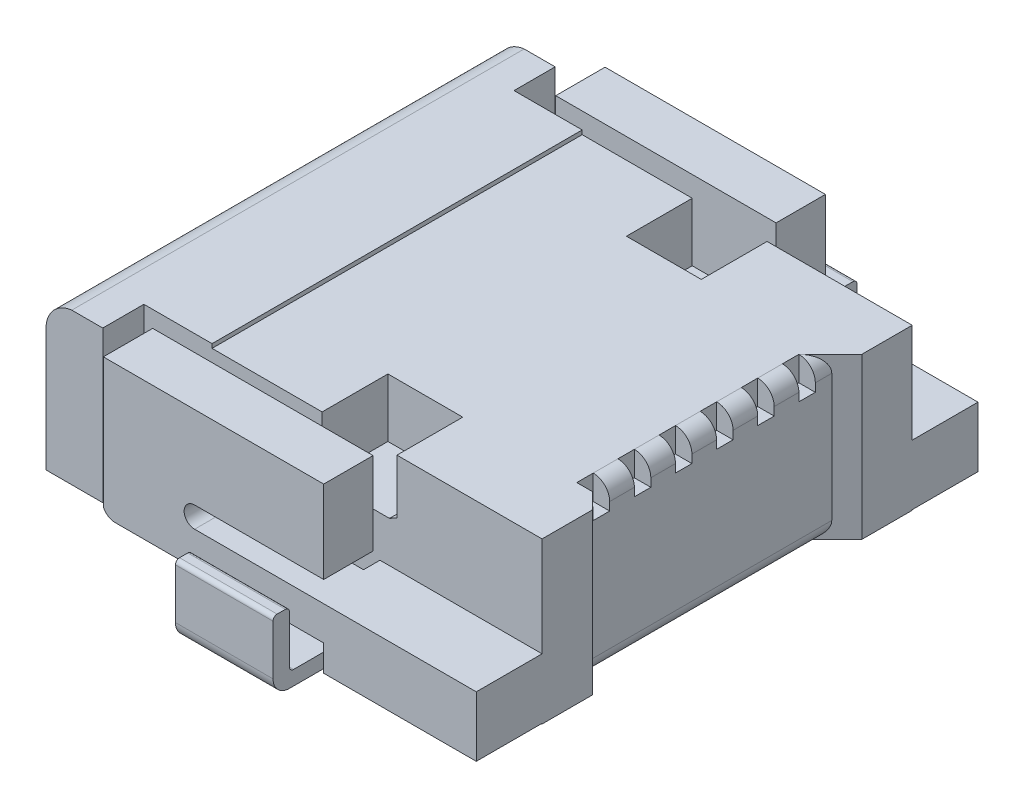
SolidWorks part; units mm, degrees
ref_plane "Front Plane" through (0, 0, 0) normal (0, 0, 1) x (1, 0, 0)
ref_plane "Top Plane" through (0, 0, 0) normal (0, 1, 0) x (1, 0, 0)
ref_plane "Right Plane" through (0, 0, 0) normal (1, 0, 0) x (0, 0, -1)
sketch "Sketch5" plane through (0, 0, 0) normal (0, 0, 1) x (1, 0, 0)
  line L0 (40.6667, 46) -> (203.3333, 46) construction
  line L1 (1.0365, 0.0671) -> (5.5705, 0.0671)
  line L2 (5.5705, 0.0671) -> (5.5705, 2.0592)
  line L3 (5.5705, 2.0592) -> (1.0365, 2.0592)
  line L4 (1.0365, 2.0592) -> (1.0365, 0.0671)
  line L5 (1.0365, 0.9096) -> (0.7294, 0.9096)
  line L6 (0.7294, 0.9096) -> (0.7294, 2.0592)
  line L7 (0.7294, 2.0592) -> (1.0365, 2.0592)
  line L8 (2.4126, 0.8573) -> (2.4126, 0.0671)
  line L9 (2.4126, 0.8573) -> (3.5997, 0.8573)
  line L10 (3.5997, 0.8573) -> (3.5997, 0.0671)
  line L11 (3.5997, 0.7994) -> (5.5705, 0.7994)
  line L12 (2.4126, 0.7994) -> (2.1463, 0.7994)
  line L13 (2.1463, 1.0542) -> (3.7156, 1.0542)
  line L14 (3.7156, 1.0542) -> (3.7156, 2.0592)
  line L15 (2.4126, 0.175) -> (1.0365, 0.175)
  line L16 (3.5997, 0.175) -> (5.5705, 0.175)
  line L17 (2.4126, 0.3858) -> (1.1847, 0.3858)
  line L18 (0.0415, 1.6702) -> (0.0415, 0.2199)
  line L19 (0.0415, 0.2199) -> (0.7294, 0.2199)
  line L20 (0.7294, 0.2199) -> (0.7294, 0.9096)
  line L21 (0.7294, 2.0592) -> (0.3527, 2.0592)
  line L22 (3.8064, 2.0592) -> (3.8064, 1.3482)
  line L23 (3.8064, 1.3482) -> (3.7156, 1.2979)
  line L24 (0.9408, 0.9096) -> (0.9408, 1.2134)
  line L25 (0.9408, 1.2134) -> (1.0365, 1.2134)
  line L26 (3.5997, 0.3858) -> (3.7156, 0.3858)
  line L27 (3.7156, 0.3858) -> (3.7156, 0.175)
  arc A0 (2.1463, 0.7994) -> (2.1463, 1.0542) centre (2.1463, 0.9268) cw
  arc A1 (0.0415, 1.6702) -> (0.3527, 2.0592) centre (0.3916, 1.7091) cw
  spline S0 degree 2 poles (1.1847, 0.3858) (1.082, 0.3886) (1.0365, 0.477) knots 0 0 0 1 1 1
extrude "Boss-Extrude1" add sketch "Sketch5" against normal blind 0.6 contours S0 L17 L8 L12 A0 L13 L14 L3 L4
sketch "Sketch7" plane through (0, 0, 0) normal (0, 0, 1) x (1, 0, 0)
  line L0 (5.5705, 0.0671) -> (5.5705, 2.0592) construction
  line L2 (3.7156, 0.3858) -> (3.7156, 0.175) construction
  line L3 (3.5997, 0.3858) -> (3.7156, 0.3858) construction
  line L4 (3.5997, 0.7994) -> (5.5705, 0.7994) construction
  line L10 (5.5705, 0.175) -> (5.5705, 0.7994)
  line L11 (3.7156, 0.175) -> (3.7156, 0.0671)
  line L12 (3.7156, 0.3858) -> (3.7156, 0.175)
  line L13 (3.5997, 0.3858) -> (3.7156, 0.3858)
  line L14 (3.5997, 0.7994) -> (5.5705, 0.7994)
  line L15 (3.5997, 0.7994) -> (3.5997, 0.3858)
  line L16 (1.0365, 0.0671) -> (5.5705, 0.0671) construction
  line L17 (3.7156, 0.0671) -> (5.5705, 0.0671)
  line L18 (5.5705, 0.0671) -> (5.5705, 0.175)
  line L20 (2.4126, 0.3858) -> (3.5997, 0.3858)
  line L21 (2.4126, 0.7994) -> (3.5997, 0.7994)
  line L24 (2.4126, 0.7994) -> (2.4126, 0.3858)
extrude "Boss-Extrude2" add sketch "Sketch7" against normal blind 0.8 separate body contours L17 L18 L10 L14 L15 L13 L12 L11
sketch "Sketch8" plane through (0, 0, 0) normal (0, 0, 1) x (1, 0, 0)
  line L0 (3.5997, 0.7994) -> (2.4126, 0.7994)
  line L1 (3.5997, 0.3858) -> (2.4126, 0.3858)
  line L2 (3.5997, 0.8573) -> (3.5997, 0.0671) construction
  line L3 (2.4126, 0.8573) -> (2.4126, 0.0671) construction
  line L4 (3.5997, 0.7994) -> (3.5997, 0.3858)
  line L5 (2.4126, 0.7994) -> (2.4126, 0.3858)
extrude "Boss-Extrude3" add sketch "Sketch8" against normal blind 0.6
sketch "Sketch11" plane through (0, 0, 0) normal (0, 1, 0) x (1, 0, 0)
  line L0 (5.5705, 0.8) -> (5.5705, 1.4131)
  line L1 (5.5705, 1.4131) -> (5.3077, 1.5403)
  line L2 (5.3077, 1.5403) -> (5.3077, 9.05)
  line L3 (3.5997, 0) -> (5.5705, 0) construction
  line L4 (5.3077, 9.05) -> (1.7077, 9.05)
  line L5 (1.7077, 9.05) -> (1.7077, 0.8)
  line L6 (1.7077, 0.8) -> (5.5705, 0.8)
  dimension "D1" = 9.05
  dimension "D2" = 3.6
ref_plane "Plane1" through (0, 0.06, 0) normal (0, 1, 0) x (1, 0, 0)
sketch "Sketch13" plane through (0, 0.06, 0) normal (0, 1, 0) x (1, 0, 0)
  line L0 (3.7156, 0) -> (1.0365, 0) construction
  line L2 (5.5705, 0.8) -> (5.5705, 1.4131) construction
  line L6 (5.3077, 3.05) -> (1.6924, 3.05)
  line L7 (5.5705, 1.4131) -> (5.3881, 1.5955)
  line L8 (5.5705, 0.8) -> (5.5705, 1.4131)
  line L9 (1.6924, 3.05) -> (1.6924, 0.8)
  line L10 (5.3881, 1.5955) -> (5.3881, 3.05)
  line L11 (1.6924, 0.8) -> (5.5705, 0.8)
  line L12 (5.3881, 3.05) -> (5.3077, 3.05)
  dimension "D1" = 3.05
extrude "Boss-Extrude5" add sketch "Sketch13" along normal up to surface (1.9992 mm away) up to face at (2.376, 2.0592, -0.3)
sketch "Sketch17" plane through (0, 0, -0.8) normal (0, 0, 1) x (1, 0, 0)
  line L0 (3.8064, 1.3482) -> (3.7156, 1.2979) construction
  line L1 (3.8064, 2.0592) -> (3.8064, 1.3482) construction
  line L2 (3.8064, 1.3482) -> (3.7156, 1.2979)
  line L3 (3.8064, 2.0592) -> (3.8064, 1.3482)
  line L4 (3.7156, 1.2979) -> (2.8963, 1.2979)
  line L5 (2.8963, 1.2979) -> (2.8963, 2.0592)
  line L6 (1.6924, 2.0592) -> (5.5705, 2.0592) construction
  line L7 (2.8963, 2.0592) -> (3.8064, 2.0592)
extrude "Cut-Extrude6" cut sketch "Sketch17" against normal blind 0.8
sketch "Sketch18" plane through (0, 0, -0.8) normal (0, 0, 1) x (1, 0, 0)
  line L0 (0.0415, 1.6702) -> (0.0415, 0.2199)
  line L1 (0.7294, 2.0592) -> (0.7294, 0.9096)
  line L5 (0.0415, 0.2199) -> (0.7294, 0.2199) construction
  line L6 (0.7294, 0.2199) -> (0.7294, 0.9096) construction
  line L9 (0.7294, 2.0592) -> (0.3527, 2.0592) construction
  line L15 (0.0415, 0.2199) -> (0.7294, 0.2199)
  line L16 (0.7294, 0.2199) -> (0.7294, 0.9096)
  line L19 (0.7294, 2.0592) -> (0.3527, 2.0592)
  arc A0 (0.3527, 2.0592) -> (0.0415, 1.6702) centre (0.3916, 1.7091) ccw construction
  arc A1 (0.3527, 2.0592) -> (0.0415, 1.6702) centre (0.3916, 1.7091) ccw
sketch "Sketch19" plane through (1.6924, 0, 0) normal (-1, 0, 0) x (0, 0, 1)
  line L0 (-3.05, 2.0592) -> (-0.8, 2.0592) construction
  line L1 (-3.05, 2.0592) -> (-0.8, 2.0592)
  line L4 (-0.8, 2.0592) -> (-3.05, 2.0592)
  line L5 (-3.05, 2.0592) -> (-3.05, 0.06)
  line L6 (-3.05, 0.06) -> (-0.8, 0.06)
  line L7 (-0.8, 0.06) -> (-0.8, 2.0592)
  line L9 (-3.05, 2.0592) -> (-3.05, 0.06)
  line L10 (-3.05, 0.06) -> (-0.8, 0.06)
  line L11 (-0.8, 0.06) -> (-0.8, 2.0592)
  dimension "D1" = 0
extrude "Boss-Extrude6" add sketch "Sketch19" along normal up to vertex (0.963 mm away) separate body up to point (0.7294, 2.0592, -0.8)
extrude "Boss-Extrude7" add sketch "Sketch18" against normal up to surface (2.25 mm away) up to face at (3.5403, 1.0596, -3.05)
sketch "Sketch20" plane through (0, 0, -0.8) normal (0, 0, 1) x (1, 0, 0)
  line L0 (1.0365, 2.0592) -> (1.0365, 0.0671) construction
  line L1 (0.7294, 0.2199) -> (0.7294, 0.9096) construction
  line L2 (1.0365, 0.9096) -> (0.7294, 0.9096) construction
  line L3 (1.0365, 2.0592) -> (1.0365, 0.0671)
  line L4 (0.7294, 0.2199) -> (0.7294, 0.9096)
  line L5 (1.0365, 0.9096) -> (0.7294, 0.9096)
  line L6 (0.7294, 0.2199) -> (0.7294, 0.06)
  line L7 (0.7294, -0.0203) -> (1.0365, -0.0203)
  line L8 (1.0365, -0.0203) -> (1.0365, 0.0671)
  line L9 (0.7294, 0.06) -> (0.7294, -0.0203)
extrude "Cut-Extrude7" cut sketch "Sketch20" against normal up to surface (2.25 mm away)
sketch "Sketch21" plane through (0, 0, -0.8) normal (0, 0, 1) x (1, 0, 0)
  line L0 (0.7294, 0.2199) -> (0.7294, 0.9096) construction
  line L1 (0.0415, 0.2199) -> (0.7294, 0.2199) construction
  line L2 (0.0415, 1.6702) -> (0.0415, 0.2199) construction
  line L3 (0.7294, 2.0592) -> (0.3527, 2.0592) construction
  line L4 (0.7294, 0.9096) -> (0.7294, 2.0592) construction
  line L5 (0.7294, 0.2199) -> (0.7294, 0.9096)
  line L6 (0.0415, 0.2199) -> (0.7294, 0.2199)
  line L7 (0.0415, 1.6702) -> (0.0415, 0.2199)
  line L8 (0.7294, 2.0592) -> (0.3527, 2.0592)
  line L9 (0.7294, 0.9096) -> (0.7294, 2.0592)
  arc A0 (0.3527, 2.0592) -> (0.0415, 1.6702) centre (0.3916, 1.7091) ccw construction
  arc A1 (0.3527, 2.0592) -> (0.0415, 1.6702) centre (0.3916, 1.7091) ccw
extrude "Boss-Extrude8" add sketch "Sketch21" along normal blind 0.5
mirror "Mirror1" of "Boss-Extrude8", "Cut-Extrude7", "Boss-Extrude7", "Boss-Extrude6", "Cut-Extrude6", "Boss-Extrude5", "Boss-Extrude3", "Boss-Extrude2", "Boss-Extrude1"
sketch "Sketch22" plane through (0, 2.0592, 0) normal (0, 1, 0) x (1, 0, 0)
  line L0 (1.5582, 5.3) -> (1.5582, 0.8)
  line L20 (2.8963, 4.5) -> (2.8963, 5.3)
  line L21 (2.8963, 5.3) -> (0.7294, 5.3)
  line L22 (0.7294, 5.3) -> (0.7294, 5.8)
  line L23 (0.7294, 5.8) -> (0.3527, 5.8)
  line L24 (0.3527, 5.8) -> (0.3527, 0.3)
  line L25 (0.3527, 0.3) -> (0.7294, 0.3)
  line L26 (0.7294, 0.3) -> (0.7294, 0.8)
  line L27 (0.7294, 0.8) -> (2.8963, 0.8)
  line L28 (2.8963, 0.8) -> (2.8963, 1.6)
  line L29 (2.8963, 1.6) -> (3.8064, 1.6)
  line L30 (3.8064, 1.6) -> (3.8064, 0.8)
  line L31 (3.8064, 0.8) -> (5.5705, 0.8)
  line L32 (5.5705, 0.8) -> (5.5705, 1.4131)
  line L33 (5.5705, 1.4131) -> (5.3881, 1.5955)
  line L34 (5.5705, 1.4131) -> (5.3881, 1.5955)
  line L35 (5.3881, 1.5955) -> (5.3881, 4.5045)
  line L36 (5.5705, 4.6869) -> (5.5705, 5.3)
  line L37 (5.5705, 5.3) -> (3.8064, 5.3)
  line L38 (3.8064, 5.3) -> (3.8064, 4.5)
  line L39 (3.8064, 4.5) -> (2.8963, 4.5)
  line L40 (2.8963, 4.5) -> (2.8963, 5.3)
  line L41 (2.8963, 5.3) -> (1.5582, 5.3)
  line L43 (5.3881, 1.5955) -> (5.3881, 4.5045)
  line L44 (5.3881, 4.5045) -> (5.5705, 4.6869)
  line L45 (5.3881, 4.5045) -> (5.5705, 4.6869)
  line L46 (0.7294, 0.3) -> (0.7294, 0.8)
  line L47 (1.5582, 0.8) -> (2.8963, 0.8)
  line L48 (2.8963, 0.8) -> (2.8963, 1.6)
  line L49 (2.8963, 1.6) -> (3.8064, 1.6)
  line L50 (3.8064, 1.6) -> (3.8064, 0.8)
  line L51 (3.8064, 0.8) -> (5.5705, 0.8)
  line L52 (5.5705, 0.8) -> (5.5705, 1.4131)
  line L56 (5.5705, 4.6869) -> (5.5705, 5.3)
  line L57 (5.5705, 5.3) -> (3.8064, 5.3)
  line L58 (3.8064, 5.3) -> (3.8064, 4.5)
  line L59 (3.8064, 4.5) -> (2.8963, 4.5)
  dimension "D1" = 0
extrude "Cut-Extrude8" cut sketch "Sketch22" against normal blind 0.05
fillet "Fillet4" radius 0.2 2 edges at (5.3881, 2.0092, -3.05) (5.3881, 0.06, -3.05)
sketch "Sketch26" plane through (0, 0, 0) normal (0, 0, 1) x (1, 0, 0)
  line L1 (3.5997, 0.8573) -> (3.5997, 0.0671) construction
  line L2 (2.4126, 0.8573) -> (2.4126, 0.0671) construction
  line L3 (2.4126, 0.8573) -> (3.5997, 0.8573) construction
  line L4 (2.4126, 0.0671) -> (2.4126, 0)
  line L5 (3.5997, 0.8573) -> (3.5997, 0.0671)
  line L6 (2.4126, 0.8573) -> (2.4126, 0.0671)
  line L7 (2.4126, 0.8573) -> (3.5997, 0.8573)
  line L8 (2.4126, 0) -> (3.5997, 0)
  line L9 (3.5997, 0) -> (3.5997, 0.0671)
  line L10 (2.4126, 0.175) -> (3.5997, 0.175)
extrude "Boss-Extrude9" add sketch "Sketch26" along normal blind 0.5 contours L10 L6 L4 L8 L9 L5
sketch "Sketch27" plane through (0, 0, 0.5) normal (0, 0, 1) x (1, 0, 0)
  line L0 (2.4126, 0.175) -> (3.5997, 0.175) construction
  line L1 (3.5997, 0.8573) -> (3.5997, 0.0671) construction
  line L2 (2.4126, 0.8573) -> (2.4126, 0.0671) construction
  line L3 (2.4126, 0.8573) -> (3.5997, 0.8573) construction
  line L4 (2.4126, 0.175) -> (3.5997, 0.175)
  line L5 (3.5997, 0.8573) -> (3.5997, 0.175)
  line L6 (2.4126, 0.8573) -> (2.4126, 0.175)
  line L7 (2.4126, 0.8573) -> (3.5997, 0.8573)
extrude "Boss-Extrude10" add sketch "Sketch27" against normal blind 0.2
fillet "Fillet6" radius 0.2 1 edges at (3.0062, 0, 0.5)
fillet "Fillet7" radius 0.05 2 edges at (3.0062, 0.8573, 0.5) (3.0062, 0.8573, 0.3)
sketch "Sketch28" plane through (2.4126, 0, 0) normal (-1, 0, 0) x (0, 0, 1)
  line L0 (-0.8, 0.3858) -> (-0.8, 0.0671) construction
  line L1 (-0.8, 0.3233) -> (-0.8, 0.1393)
  line L2 (0, 0.175) -> (-0.5527, 0.175)
  line L3 (0, 0) -> (-0.5527, 0)
  line L4 (0, 0.175) -> (0, 0)
  arc A0 (-0.5527, 0) -> (-0.8, 0.1393) centre (-0.5056, 0.3729) cw
  arc A1 (-0.5527, 0.175) -> (-0.8, 0.3233) centre (-0.4668, 0.5985) cw
extrude "Boss-Extrude11" add sketch "Sketch28" against normal up to surface (1.1871 mm away) up to face at (3.5997, 0.4287, 0.3046)
ref_plane "Plane3" through (0, 0, -3.05) normal (0, 0, 1) x (1, 0, 0)
mirror "Mirror6" about plane through (0, 0, -3.05) normal (0, 0, 1) of "Boss-Extrude11", "Fillet7", "Fillet6", "Boss-Extrude10", "Boss-Extrude9"
fillet "Fillet8" radius 0.05 1 edges at (3.0062, 0.175, 0.3)
fillet "Fillet9" radius 0.05 1 edges at (3.0062, 0.175, -6.4)
sketch "Sketch29" plane through (0, 2.0092, 0) normal (0, 1, 0) x (1, 0, 0)
  line L0 (5.8595, 3.8045) -> (5.8595, 3.6045)
  line L1 (5.1881, 4.3045) -> (5.8595, 4.3045)
  line L2 (5.1881, 4.3045) -> (5.1881, 4.1045)
  line L3 (5.1881, 4.1045) -> (5.8595, 4.1045)
  line L4 (5.8595, 4.3045) -> (5.8595, 4.1045)
  line L5 (5.1881, 3.6045) -> (5.8595, 3.6045)
  line L6 (5.1881, 3.8045) -> (5.1881, 3.6045)
  line L7 (5.1881, 3.8045) -> (5.8595, 3.8045)
  line L8 (5.8595, 3.3045) -> (5.8595, 3.1045)
  line L9 (5.1881, 3.1045) -> (5.8595, 3.1045)
  line L10 (5.1881, 3.3045) -> (5.1881, 3.1045)
  line L11 (5.1881, 3.3045) -> (5.8595, 3.3045)
  line L12 (5.8595, 2.8045) -> (5.8595, 2.6045)
  line L13 (5.1881, 2.6045) -> (5.8595, 2.6045)
  line L14 (5.1881, 2.8045) -> (5.1881, 2.6045)
  line L15 (5.1881, 2.8045) -> (5.8595, 2.8045)
  line L16 (5.8595, 2.3045) -> (5.8595, 2.1045)
  line L17 (5.1881, 2.1045) -> (5.8595, 2.1045)
  line L18 (5.1881, 2.3045) -> (5.1881, 2.1045)
  line L19 (5.1881, 2.3045) -> (5.8595, 2.3045)
  line L20 (5.8595, 1.8045) -> (5.8595, 1.6045)
  line L21 (5.1881, 1.6045) -> (5.8595, 1.6045)
  line L22 (5.1881, 1.8045) -> (5.1881, 1.6045)
  line L23 (5.1881, 1.8045) -> (5.8595, 1.8045)
  dimension "D1" = 0.2
  dimension "D2" = 6
extrude "Cut-Extrude9" cut sketch "Sketch29" against normal blind 0.3
sketch "Sketch30" plane through (0.0415, 0, 0) normal (-1, 0, 0) x (0, 0, 1)
  line L1 (-3.05, -0.4911) -> (-3.05, 2.6862) construction
  line L2 (-4.835, 0.2199) -> (-4.835, 0.9096)
  line L3 (-5.8, 0.2199) -> (-0.3, 0.2199) construction
  line L4 (-4.835, 0.9096) -> (-4.335, 0.9096)
  line L5 (-4.335, 0.9096) -> (-4.335, 1.2296)
  line L6 (-4.335, 1.2296) -> (-1.765, 1.2296)
  line L7 (-1.265, 0.2199) -> (-1.265, 0.9096)
  line L8 (-1.265, 0.9096) -> (-1.765, 0.9096)
  line L9 (-1.765, 0.9096) -> (-1.765, 1.2296)
  line L10 (-4.835, 0.2199) -> (-1.265, 0.2199)
  point P13 (-3.05, 1.2296)
  dimension "D1" = 0.5
  dimension "D2" = 0.32
  dimension "D3" = 1.785
extrude "Cut-Extrude10" cut sketch "Sketch30" against normal up to surface (0.688 mm away) up to face at (0.7294, 1.312, -3.05)
sketch "Sketch31" plane through (1.0365, 0, 0) normal (-1, 0, 0) x (0, 0, 1)
  line L0 (-5.3, 0.9096) -> (-0.8, 0.9096) construction
  line L1 (-4.385, 0.9096) -> (-4.185, 0.9096)
  line L2 (-4.835, 0.9096) -> (-4.835, 0.2199) construction
  line L3 (-4.385, 0.9096) -> (-4.185, 0.9096)
  line L4 (-4.385, 0.9096) -> (-4.385, 0.3696)
  line L5 (-4.385, 0.3696) -> (-4.185, 0.3696)
  line L6 (-4.185, 0.9096) -> (-4.185, 0.3696)
  line L7 (-3.885, 0.9096) -> (-3.685, 0.9096)
  line L8 (-3.685, 0.9096) -> (-3.685, 0.3696)
  line L9 (-3.885, 0.9096) -> (-3.885, 0.3696)
  line L10 (-3.885, 0.3696) -> (-3.685, 0.3696)
  line L11 (-3.385, 0.9096) -> (-3.185, 0.9096)
  line L12 (-3.185, 0.9096) -> (-3.185, 0.3696)
  line L13 (-3.385, 0.9096) -> (-3.385, 0.3696)
  line L14 (-3.385, 0.3696) -> (-3.185, 0.3696)
  line L15 (-2.885, 0.9096) -> (-2.685, 0.9096)
  line L16 (-2.685, 0.9096) -> (-2.685, 0.3696)
  line L17 (-2.885, 0.9096) -> (-2.885, 0.3696)
  line L18 (-2.885, 0.3696) -> (-2.685, 0.3696)
  line L19 (-2.385, 0.9096) -> (-2.185, 0.9096)
  line L20 (-2.185, 0.9096) -> (-2.185, 0.3696)
  line L21 (-2.385, 0.9096) -> (-2.385, 0.3696)
  line L22 (-2.385, 0.3696) -> (-2.185, 0.3696)
  line L23 (-1.885, 0.9096) -> (-1.685, 0.9096)
  line L24 (-1.685, 0.9096) -> (-1.685, 0.3696)
  line L25 (-1.885, 0.9096) -> (-1.885, 0.3696)
  line L26 (-1.885, 0.3696) -> (-1.685, 0.3696)
  line M5 (-0.8, 0.9096) -> (-5.3, 0.9096)
  dimension "D1" = 0.2
  dimension "D2" = 0.54
  dimension "D3" = 0.45
  dimension "D4" = 6
extrude "Boss-Extrude12" add sketch "Sketch31" along normal blind 0.05 contours L6 L4 L5 M5 | L9 L10 L8 M5 | L13 L14 L12 M5 | L17 L18 L16 M5 | L21 L22 L20 M5 | L25 L26 L24 M5
sketch "Sketch32" plane through (0.9865, 0, 0) normal (-1, 0, 0) x (0, 0, 1)
  line L0 (-4.385, 0.9096) -> (-4.385, 0.3696) construction
  line L1 (-4.385, 0.7998) -> (-4.185, 0.7998)
  line L2 (-4.385, 0.7998) -> (-4.385, 0.6396)
  line L3 (-4.385, 0.6396) -> (-4.185, 0.6396)
  line L4 (-4.185, 0.7998) -> (-4.185, 0.6396)
  line L5 (-4.185, 0.9096) -> (-4.185, 0.3696) construction
extrude "Boss-Extrude13" add sketch "Sketch32" along normal blind 0.01
pattern_linear "LPattern1" count 6 spacing 0.5 along (0, 0, 1) of "Boss-Extrude13"
